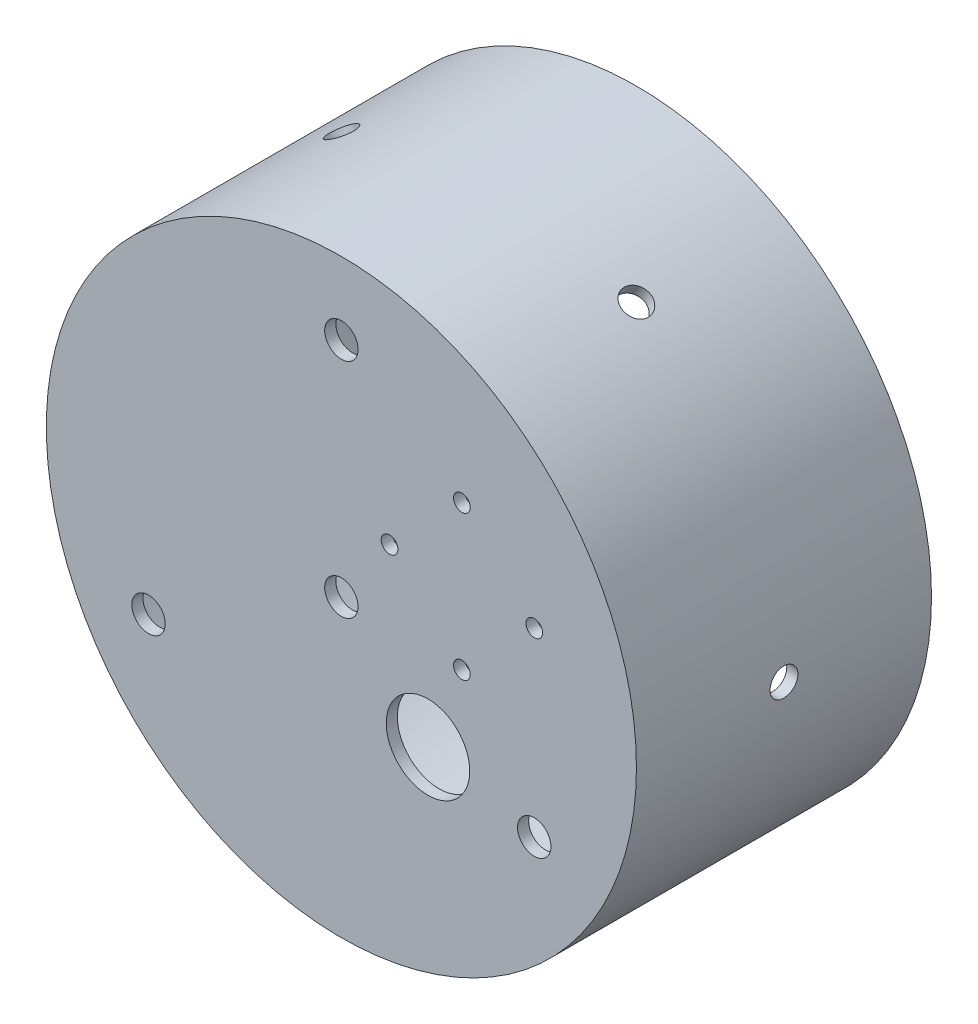
SolidWorks part; units mm, degrees
ref_plane "Front Plane" through (0, 0, 0) normal (0, 0, 1) x (1, 0, 0)
ref_plane "Top Plane" through (0, 0, 0) normal (0, 1, 0) x (1, 0, 0)
ref_plane "Right Plane" through (0, 0, 0) normal (1, 0, 0) x (0, 0, -1)
sketch "Sketch1" plane through (0, 0, 0) normal (0, 0, 1) x (1, 0, 0)
  circle A0 centre (0, 0) radius 53
  dimension "D1" = 106
extrude "Boss-Extrude1" add sketch "Sketch1" along normal blind 53
sketch "Sketch2" plane through (0, 0, 53) normal (0, 0, 1) x (1, 0, 0)
  line L0 (0, 40) -> (0, 0) construction
  line L1 (0, 0) -> (34.641, -20) construction
  line L2 (0, 0) -> (-34.641, -20) construction
  circle A0 centre (0, 0) radius 40 construction
  circle A1 centre (0, 40) radius 3
  circle A2 centre (34.641, -20) radius 3
  circle A3 centre (-34.641, -20) radius 3
  circle A4 centre (0, 0) radius 3
  point P11 (0, 0)
  dimension "D1" = 80
  dimension "D2" = 6
  dimension "D4" = 120
  dimension "D5" = 6
  dimension "D3" = 3
extrude "Cut-Extrude1" cut sketch "Sketch2" against normal through all
sketch "Sketch6" plane through (0, 0, 53) normal (0, 0, 1) x (1, 0, 0)
  line L0 (0, 0) -> (53, 0) construction
  line L1 (21.6506, 12.5) -> (0, 0) construction
  line L2 (21.6506, 12.5) -> (8.6506, 12.5) construction
  line L3 (8.6506, 12.5) -> (34.6506, 12.5) construction
  circle A0 centre (21.6506, 12.5) radius 15 construction
  circle A1 centre (0, 0) radius 53 construction
  circle A2 centre (21.6506, 12.5) radius 11 construction
  circle A3 centre (21.6506, 12.5) radius 9 construction
  circle A4 centre (21.6506, 25.5) radius 1.5
  circle A5 centre (21.6506, 12.5) radius 13 construction
  circle A6 centre (34.6506, 12.5) radius 1.5
  circle A7 centre (21.6506, -0.5) radius 1.5
  circle A8 centre (8.6506, 12.5) radius 1.5
  point P24 (21.6506, 12.5)
  dimension "D1" = 30
  dimension "D6" = 3
  dimension "D2" = 30
  dimension "D3" = 25
  dimension "D7" = 13
  dimension "D4" = 4
  dimension "D5" = 2
  dimension "D8" = 4
sketch "Sketch7" plane through (0, 0, 53) normal (0, 0, 1) x (1, 0, 0)
  line L0 (0, 0) -> (0, -20.1377) construction
  line L1 (0, 0) -> (15.5563, -15.5563) construction
  circle A0 centre (15.5563, -15.5563) radius 7.5
  dimension "D3" = 15
  dimension "D1" = 45
  dimension "D2" = 22
shell "Shell4" thickness 2
extrude "Cut-Extrude3" cut sketch "Sketch6" against normal blind 10
extrude "Cut-Extrude4" cut sketch "Sketch7" against normal blind 10
sketch "Sketch8" plane through (0, 0, 0) normal (0, 0, -1) x (-1, 0, 0)
  circle A0 centre (0, 0) radius 51
  dimension "D1" = 102
extrude "Cut-Extrude5" cut sketch "Sketch8" against normal blind 51
ref_plane "Plane1" through (-53, 0, 0) normal (-1, 0, 0) x (0, 0, 1)
sketch "Sketch9" plane through (-53, 0, 0) normal (-1, 0, 0) x (0, 0, 1)
  circle A0 centre (26.5, 0) radius 2.5
  dimension "D2" = 5
  dimension "D1" = 26.5
extrude "Cut-Extrude6" cut sketch "Sketch9" against normal blind 51
pattern_circular "CirPattern1" count 6 over 360 about axis through (0, 0, 0) along (0, 0, 1) of "Cut-Extrude6"
